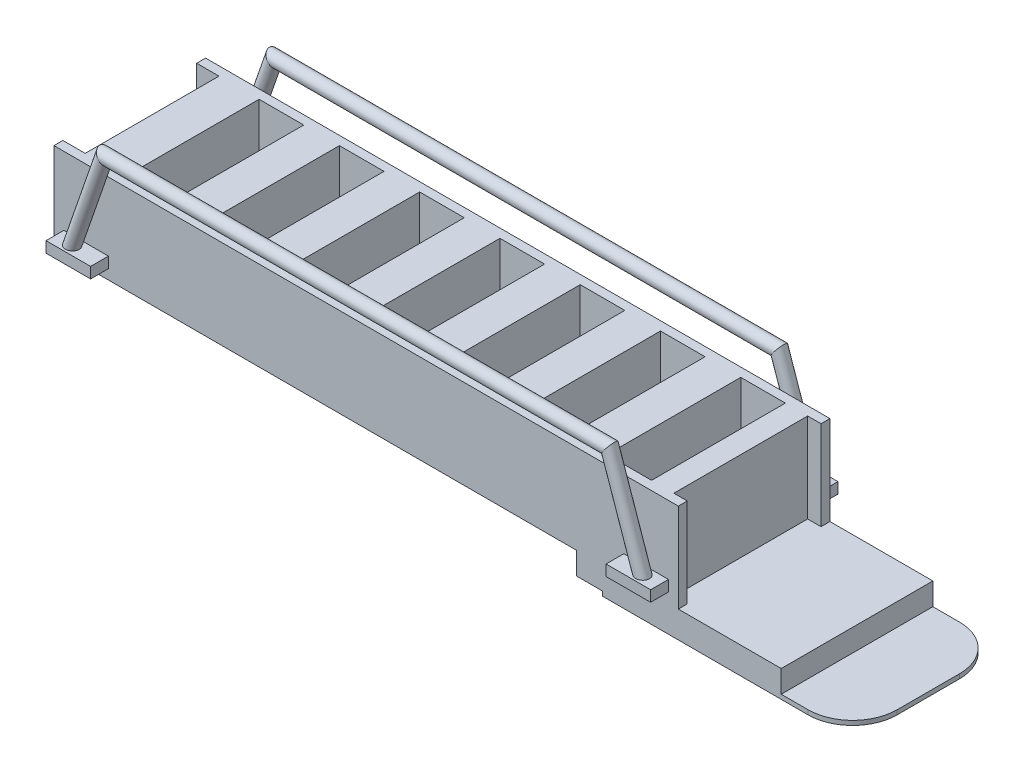
SolidWorks part; units mm, degrees
material "A286 Iron Base Superalloy"
ref_plane "Front Plane" through (0, 0, 0) normal (0, 0, 1) x (1, 0, 0)
ref_plane "Top Plane" through (0, 0, 0) normal (0, 1, 0) x (1, 0, 0)
ref_plane "Right Plane" through (0, 0, 0) normal (1, 0, 0) x (0, 0, -1)
sketch "Sketch1" plane through (0, 0, 0) normal (0, 1, 0) x (1, 0, 0)
  line L1 (0, 0) -> (140, 0)
  line L2 (0, 0) -> (0, 2)
  line L3 (0, 2) -> (140, 2)
  line L4 (140, 0) -> (140, 2)
extrude "Boss-Extrude3" add sketch "Sketch1" along normal blind 20
sketch "Sketch3" plane through (0, 0, -2) normal (0, 0, -1) x (-1, 0, 0)
  line L0 (-140, 0) -> (0, 0) construction
  line L1 (-140, 20) -> (-132, 20)
  line L2 (-140, 20) -> (-140, 0)
  line L3 (-140, 0) -> (-132, 0)
  line L4 (-132, 20) -> (-132, 0)
  line L6 (-140, 20) -> (0, 20) construction
  line L8 (-122, 20) -> (-114, 20)
  line L9 (-122, 20) -> (-122, 0)
  line L10 (-122, 0) -> (-114, 0)
  line L11 (-114, 20) -> (-114, 0)
  line L12 (-104, 20) -> (-96, 20)
  line L13 (-104, 20) -> (-104, 0)
  line L14 (-104, 0) -> (-96, 0)
  line L15 (-96, 20) -> (-96, 0)
  line L17 (-86, 20) -> (-78, 20)
  line L18 (-86, 20) -> (-86, 0)
  line L19 (-86, 0) -> (-78, 0)
  line L20 (-78, 20) -> (-78, 0)
  line L22 (-68, 20) -> (-60, 20)
  line L23 (-68, 20) -> (-68, 0)
  line L24 (-68, 0) -> (-60, 0)
  line L25 (-60, 20) -> (-60, 0)
  line L27 (-50, 20) -> (-42, 20)
  line L28 (-50, 20) -> (-50, 0)
  line L29 (-50, 0) -> (-42, 0)
  line L30 (-42, 20) -> (-42, 0)
  line L32 (-32, 20) -> (-24, 20)
  line L33 (-32, 20) -> (-32, 0)
  line L34 (-32, 0) -> (-24, 0)
  line L35 (-24, 20) -> (-24, 0)
  line L37 (-14, 20) -> (-5, 20)
  line L38 (-14, 20) -> (-14, 0)
  line L39 (-14, 0) -> (-5, 0)
  line L40 (-5, 20) -> (-5, 0)
extrude "Boss-Extrude4" add sketch "Sketch3" along normal blind 30
sketch "Sketch4" plane through (0, 0, -32) normal (0, 0, -1) x (-1, 0, 0)
  line L1 (-140, 0) -> (0, 0)
  line L2 (-140, 0) -> (-140, 20)
  line L3 (-140, 20) -> (0, 20)
  line L4 (0, 0) -> (0, 20)
extrude "Boss-Extrude6" add sketch "Sketch4" along normal blind 2
sketch "Sketch6" plane through (140, 0, 0) normal (1, 0, 0) x (0, 0, -1)
  line L0 (0, 20) -> (1.8304, 20)
  line L1 (0, 20) -> (34, 20) construction
  line L2 (0, 20) -> (0, 0) construction
  line L3 (0, 20) -> (0, 18)
  line L5 (2, 20.0508) -> (32, 20.0508)
  line L6 (2, 20.0508) -> (2, -0.6445)
  line L7 (2, -0.6445) -> (32, -0.6445)
  line L8 (32, 20.0508) -> (32, -0.6445)
extrude "Cut-Extrude4" cut sketch "Sketch6" against normal blind 3
sketch "Sketch8" plane through (0, 0, 0) normal (0, -1, 0) x (1, 0, 0)
  line L0 (0, 0) -> (140, 0) construction
  line L1 (117.1322, 0) -> (163.0737, 0)
  line L2 (117.1322, 0) -> (117.1322, -34)
  line L3 (117.1322, -34) -> (163.0737, -34)
  line L4 (163.0737, 0) -> (163.0737, -34)
extrude "Boss-Extrude7" add sketch "Sketch8" along normal blind 5
sketch "Sketch9" plane through (0, 0, 0) normal (0, 0, 1) x (1, 0, 0)
  line L1 (2.21, 4.6524) -> (12.21, 4.6524)
  line L2 (2.21, 4.6524) -> (2.21, 2.2115)
  line L3 (2.21, 2.2115) -> (12.21, 2.2115)
  line L4 (12.21, 4.6524) -> (12.21, 2.2115)
extrude "Boss-Extrude8" add sketch "Sketch9" along normal blind 4
sketch "Sketch10" plane through (0, 4.6524, 0) normal (0, 1, 0) x (1, 0, 0)
  line L0 (12.21, -4) -> (12.21, 0) construction
  line L1 (2.21, -4) -> (12.21, -4)
  line L2 (2.21, -4) -> (2.21, -2)
  line L3 (2.21, -2) -> (12.21, -2)
  line L4 (12.21, -4) -> (12.21, -2)
ref_plane "Plane1" through (0, 0, 4) normal (0, 0, 1) x (1, 0, 0)
ref_plane "Plane2" through (0, 0, 2) normal (0, 0, 1) x (1, 0, 0)
sketch "Sketch35" plane through (0, 0, 2) normal (0, 0, 1) x (1, 0, 0)
  line L0 (5.6441, 3.4475) -> (13.3598, 25.7545)
  line L1 (13.3598, 25.7545) -> (70, 25.7545)
sweep "Sweep4" add path "Sketch35" circular profile diameter 3 parameters "D3"=3
ref_plane "Plane3" through (70, 0, 0) normal (1, 0, 0) x (0, 0, -1)
ref_plane "Plane4" through (0, 0, -16) normal (0, 0, 1) x (1, 0, 0)
mirror "Mirror9" about plane through (70, 0, 0) normal (1, 0, 0) of "Boss-Extrude8", "Sweep4"
ref_plane "Plane6" through (0, 0, -17) normal (0, 0, 1) x (1, 0, 0)
mirror "Mirror10" about plane through (0, 0, -17) normal (0, 0, 1) of "Mirror9", "Boss-Extrude8", "Sweep4"
sketch "Sketch75" plane through (0, -5, 0) normal (0, -1, 0) x (1, 0, 0)
  line L0 (163.0737, 0) -> (117.1322, 0) construction
  line L1 (123.0206, 0) -> (179.0802, 0)
  line L2 (123.0206, 0) -> (123.0206, -34)
  line L3 (123.0206, -34) -> (179.0802, -34)
  line L4 (179.0802, 0) -> (179.0802, -34)
extrude "Boss-Extrude11" add sketch "Sketch75" along normal blind 1
ref_plane "Plane7" through (0, -1, 0) normal (0, -1, 0) x (-1, 0, 0)
ref_plane "Plane8" through (0, -0.7, 0) normal (0, -1, 0) x (-1, 0, 0)
ref_plane "Plane9" through (0, 0, -17) normal (0, 0, -1) x (-1, 0, 0)
sketch "Sketch84" plane through (0, -6, 0) normal (0, -1, 0) x (1, 0, 0)
  circle A0 centre (165.8213, -17) radius 2.5
extrude "Boss-Extrude12" add sketch "Sketch84" along normal blind 10
fillet "Fillet1" radius 10 2 edges at (179.0802, -5.5, -34) (179.0802, -5.5, 0)
